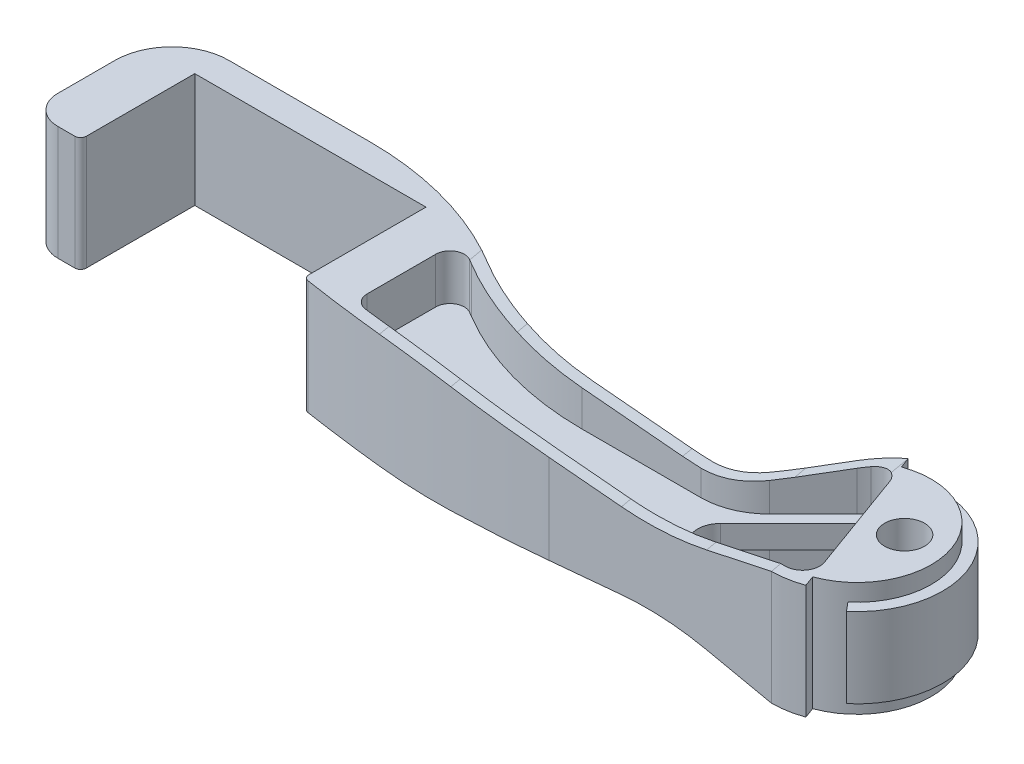
SolidWorks part; units mm, degrees
ref_plane "Alzado" through (0, 0, 0) normal (0, 0, 1) x (1, 0, 0)
ref_plane "Planta" through (0, 0, 0) normal (0, 1, 0) x (1, 0, 0)
ref_plane "Vista lateral" through (0, 0, 0) normal (1, 0, 0) x (0, 0, -1)
sketch "Croquis1" plane through (0, 0, 0) normal (0, 1, 0) x (1, 0, 0)
  line L0 (-65, 15) -> (-40.2965, 15)
  line L1 (-75, -15) -> (75, -15) construction
  line L2 (-75, -15) -> (-75, 15) construction
  line L3 (-75, 15) -> (75, 15) construction
  line L4 (75, -15) -> (75, 15) construction
  line L5 (-75, -15) -> (75, 15) construction
  line L6 (-75, 15) -> (75, -15) construction
  line L7 (13.7868, 0) -> (34.6447, 0)
  line L8 (41.7157, 2.9289) -> (49.3934, 10.6066)
  line L9 (60, -15) -> (21, -15)
  line L10 (-25.5, -10.5178) -> (-25.5, 10)
  line L11 (-25.5, 10) -> (-66, 10)
  line L12 (-66, 10) -> (-66, -9)
  line L13 (-67, -10) -> (-70, -10)
  line L14 (-75, -5) -> (-75, 5)
  line L18 (57.4617, 6.9739) -> (62.5383, -6.9739)
  line L19 (59.7192, -11) -> (43.109, -11)
  line L20 (40.2805, -4.1716) -> (52.5213, 8.0692)
  line L21 (60, 0) -> (60, 15) construction
  line L22 (57.4617, 6.9739) -> (54.8697, 14.0954) construction
  line L23 (62.5383, -6.9739) -> (65.1303, -14.0954) construction
  line L24 (60, 0) -> (69.6418, -11.4907) construction
  line L25 (54.8697, 14.0954) -> (55.5537, 12.216)
  line L26 (60, 15) -> (60, 13)
  line L27 (65.1303, -14.0954) -> (64.4463, -12.216)
  line L28 (69.6418, -11.4907) -> (68.3562, -9.9586)
  line L29 (60, 0) -> (66.108, 2.2231) construction
  arc A0 (-40.2965, 15) -> (-11.9671, 7.1429) centre (-40.2965, -40) cw
  arc A1 (-11.9671, 7.1429) -> (13.7868, 0) centre (13.7868, 50) ccw
  arc A3 (49.3934, 10.6066) -> (54.8697, 14.0954) centre (60, 0) cw
  arc A4 (21, -15) -> (-24.6522, -11.5061) centre (21, 285) cw
  arc A5 (-24.6522, -11.5061) -> (-25.5, -10.5178) centre (-24.5, -10.5178) cw
  arc A6 (-66, -9) -> (-67, -10) centre (-67, -9) cw
  arc A7 (-75, 5) -> (-65, 15) centre (-65, 5) cw
  arc A8 (-75, -5) -> (-70, -10) centre (-70, -5) ccw
  arc A9 (41.7157, 2.9289) -> (34.6447, 0) centre (34.6447, 10) cw
  arc A10 (43.109, -11) -> (40.2805, -4.1716) centre (43.109, -7) cw
  arc A11 (57.4617, 6.9739) -> (52.5213, 8.0692) centre (54.6426, 5.9479) ccw
  arc A12 (62.5383, -6.9739) -> (59.7192, -11) centre (59.7192, -8) cw
  arc A14 (65.1303, -14.0954) -> (60, -15) centre (60, 0) cw
  arc A15 (60, 15) -> (69.6418, -11.4907) centre (60, 0) cw
  arc A16 (64.4463, -12.216) -> (68.3562, -9.9586) centre (60, 0) ccw
  arc A17 (60, 13) -> (55.5537, 12.216) centre (60, 0) ccw
  circle A18 centre (66.108, 2.2231) radius 3.5
  point P0 (0, 0)
  point P33 (-75, -10)
  point P36 (60, 0)
  point P37 (60, 0)
  point P38 (60, 0)
  point P51 (38.7868, 0)
  dimension "D3" = 10
  dimension "D4" = 5
  dimension "D6" = 1
  dimension "D10" = 55
  dimension "D11" = 50
  dimension "D13" = 10
  dimension "D14" = 15
  dimension "D16" = 300
  dimension "D17" = 1
  dimension "D21" = 4
  dimension "D22" = 3
  dimension "D23" = 3
  dimension "D24" = 13
  dimension "D26" = 6.5
  dimension "D27" = 7
  dimension "D1" = 150
  dimension "D2" = 30
  dimension "D5" = 10
  dimension "D7" = 19
  dimension "D8" = 3
  dimension "D9" = 40.5
  dimension "D12" = 25
  dimension "D15" = 39
  dimension "D18" = 135
  dimension "D19" = 20
  dimension "D20" = 4
  dimension "D25" = 20
extrude "Saliente-Extruir1" add sketch "Croquis1" along normal mid plane 4
sketch "Croquis2" plane through (0, 0, 0) normal (0, 1, 0) x (1, 0, 0)
  line L0 (54.8697, 14.0954) -> (55.5537, 12.216) construction
  line L1 (41.7157, 2.9289) -> (49.3934, 10.6066) construction
  line L2 (13.7868, 0) -> (34.6447, 0) construction
  line L3 (60, -15) -> (21, -15) construction
  line L4 (-65, 15) -> (-40.2965, 15) construction
  line L5 (-25.5, -10.5178) -> (-25.5, 10) construction
  line L6 (-25.5, 10) -> (-66, 10) construction
  line L7 (-66, 10) -> (-66, -9) construction
  line L8 (-67, -10) -> (-70, -10) construction
  line L9 (-75, -5) -> (-75, 5) construction
  line L10 (54.8697, 14.0954) -> (55.5537, 12.216)
  line L11 (41.7157, 2.9289) -> (49.3934, 10.6066)
  line L12 (13.7868, 0) -> (34.6447, 0)
  line L13 (60, -15) -> (21, -15)
  line L14 (-65, 15) -> (-40.2965, 15)
  line L15 (-25.5, -10.5178) -> (-25.5, 10)
  line L16 (-25.5, 10) -> (-66, 10)
  line L17 (-66, 10) -> (-66, -9)
  line L18 (-67, -10) -> (-70, -10)
  line L19 (-75, -5) -> (-75, 5)
  line L20 (65.1303, -14.0954) -> (64.4463, -12.216) construction
  line L21 (65.1303, -14.0954) -> (64.4463, -12.216)
  line L22 (13.7868, -2) -> (34.6447, -2)
  line L23 (43.1299, 1.5147) -> (50.8076, 9.1924)
  line L24 (60, -13) -> (21, -13)
  line L25 (-17.5, 3.7074) -> (-17.5, -8.2989)
  line L26 (63.2627, -8.9641) -> (56.7373, 8.9641)
  arc A0 (-25.5, -10.5178) -> (-24.6522, -11.5061) centre (-24.5, -10.5178) ccw construction
  circle A1 centre (66.108, 2.2231) radius 3.5 construction
  arc A2 (54.8697, 14.0954) -> (49.3934, 10.6066) centre (60, 0) ccw construction
  arc A3 (34.6447, 0) -> (41.7157, 2.9289) centre (34.6447, 10) ccw construction
  arc A4 (60, -15) -> (65.1303, -14.0954) centre (60, 0) ccw construction
  arc A5 (-24.6522, -11.5061) -> (21, -15) centre (21, 285) ccw construction
  arc A6 (-11.9671, 7.1429) -> (13.7868, 0) centre (13.7868, 50) ccw construction
  arc A7 (-11.9671, 7.1429) -> (-40.2965, 15) centre (-40.2965, -40) ccw construction
  arc A8 (-67, -10) -> (-66, -9) centre (-67, -9) ccw construction
  arc A9 (-75, -5) -> (-70, -10) centre (-70, -5) ccw construction
  arc A10 (-65, 15) -> (-75, 5) centre (-65, 5) ccw construction
  arc A11 (-25.5, -10.5178) -> (-24.6522, -11.5061) centre (-24.5, -10.5178) ccw
  circle A12 centre (66.108, 2.2231) radius 3.5
  arc A13 (54.8697, 14.0954) -> (49.3934, 10.6066) centre (60, 0) ccw
  arc A14 (34.6447, 0) -> (41.7157, 2.9289) centre (34.6447, 10) ccw
  arc A15 (60, -15) -> (65.1303, -14.0954) centre (60, 0) ccw
  arc A16 (-24.6522, -11.5061) -> (21, -15) centre (21, 285) ccw
  arc A17 (-11.9671, 7.1429) -> (13.7868, 0) centre (13.7868, 50) ccw
  arc A18 (-11.9671, 7.1429) -> (-40.2965, 15) centre (-40.2965, -40) ccw
  arc A19 (-67, -10) -> (-66, -9) centre (-67, -9) ccw
  arc A20 (-75, -5) -> (-70, -10) centre (-70, -5) ccw
  arc A21 (-65, 15) -> (-75, 5) centre (-65, 5) ccw
  arc A22 (64.4463, -12.216) -> (55.5537, 12.216) centre (60, 0) ccw
  arc A23 (-12.9973, 5.4286) -> (-13.7477, 5.8712) centre (-40.2965, -40) ccw
  arc A24 (-12.9973, 5.4286) -> (13.7868, -2) centre (13.7868, 50) ccw
  arc A25 (34.6447, -2) -> (43.1299, 1.5147) centre (34.6447, 10) ccw
  arc A26 (52.0937, 10.3194) -> (50.8076, 9.1924) centre (60, 0) ccw
  arc A27 (-15.3046, -10.7803) -> (21, -13) centre (21, 285) ccw
  arc A28 (60, -13) -> (60.5767, -12.9872) centre (60, 0) ccw
  arc A29 (-12.9973, 5.4286) -> (-40.2965, 13) centre (-40.2965, -40) ccw construction
  arc A30 (-24.3478, -9.5294) -> (21, -13) centre (21, 285) ccw construction
  arc A31 (55.5537, 12.216) -> (50.8076, 9.1924) centre (60, 0) ccw construction
  arc A32 (56.7373, 8.9641) -> (52.0937, 10.3194) centre (53.9183, 7.938) ccw
  arc A33 (60, -13) -> (64.4463, -12.216) centre (60, 0) ccw construction
  arc A34 (63.2627, -8.9641) -> (60.5767, -12.9872) centre (60.4436, -9.9902) cw
  arc A35 (-13.7477, 5.8712) -> (-17.5, 3.7074) centre (-15, 3.7074) ccw
  arc A36 (-17.5, -8.2989) -> (-15.3046, -10.7803) centre (-15, -8.2989) ccw
  dimension "D1" = 2
  dimension "D4" = 3
  dimension "D5" = 3
  dimension "D6" = 2.5
  dimension "D7" = 2.5
  dimension "D3" = 8
  dimension "D2" = 2
extrude "Saliente-Extruir2" add sketch "Croquis2" along normal mid plane 20
sketch "Croquis3" plane through (0, 0, 0) normal (0, 1, 0) x (1, 0, 0)
  line L0 (69.6418, -11.4907) -> (68.3562, -9.9586) construction
  line L1 (60, 15) -> (60, 13) construction
  line L2 (69.6418, -11.4907) -> (68.3562, -9.9586)
  line L3 (60, 15) -> (60, 13)
  arc A0 (69.6418, -11.4907) -> (60, 15) centre (60, 0) ccw construction
  arc A1 (69.6418, -11.4907) -> (60, 15) centre (60, 0) ccw
  arc A2 (68.3562, -9.9586) -> (60, 13) centre (60, 0) ccw
extrude "Saliente-Extruir3" add sketch "Croquis3" along normal mid plane 14
sketch "Croquis4" plane through (0, 0, 15) normal (0, 0, 1) x (1, 0, 0)
  line L1 (60, 10) -> (60, -10) construction
  line L2 (60, 10) -> (-10, 10)
  line L3 (60, 10) -> (60, -10) construction
  line L4 (60, 10) -> (48.6517, 7.5772)
  line L5 (33.7402, 6.6757) -> (3.4163, 9.3988)
  line L6 (16.5, 0) -> (-16.5, 0) construction
  line L7 (60, -10) -> (-10, -10)
  line L8 (33.7402, -6.6757) -> (3.4163, -9.3988)
  line L9 (60, -10) -> (48.6517, -7.5772)
  arc A1 (3.4163, 9.3988) -> (-10, 10) centre (-10, -140) ccw
  arc A2 (48.6517, 7.5772) -> (33.7402, 6.6757) centre (38.2123, 56.4753) cw
  arc A3 (3.4163, -9.3988) -> (-10, -10) centre (-10, 140) cw
  arc A4 (48.6517, -7.5772) -> (33.7402, -6.6757) centre (38.2123, -56.4753) ccw
  point P12 (41.264, 6)
  dimension "D2" = 6
  dimension "D3" = 150
  dimension "D5" = 50
  dimension "D1" = 70
  dimension "D4" = 38
sketch "Croquis5" plane through (0, 0, 0) normal (0, 1, 0) x (1, 0, 0)
  line L0 (60, -15) -> (54.8697, 14.0954) construction
  arc A0 (60, -15) -> (65.1303, -14.0954) centre (60, 0) ccw construction
  arc A1 (54.8697, 14.0954) -> (49.3934, 10.6066) centre (60, 0) ccw construction
  arc A2 (60, -15) -> (65.1303, -14.0954) centre (60, 0) ccw
  arc A3 (54.8697, 14.0954) -> (49.3934, 10.6066) centre (60, 0) ccw
extrude "Cortar-Extruir1" cut sketch "Croquis4" along direction (-0.1736, 0, -0.9848) on the side against the normal through all
